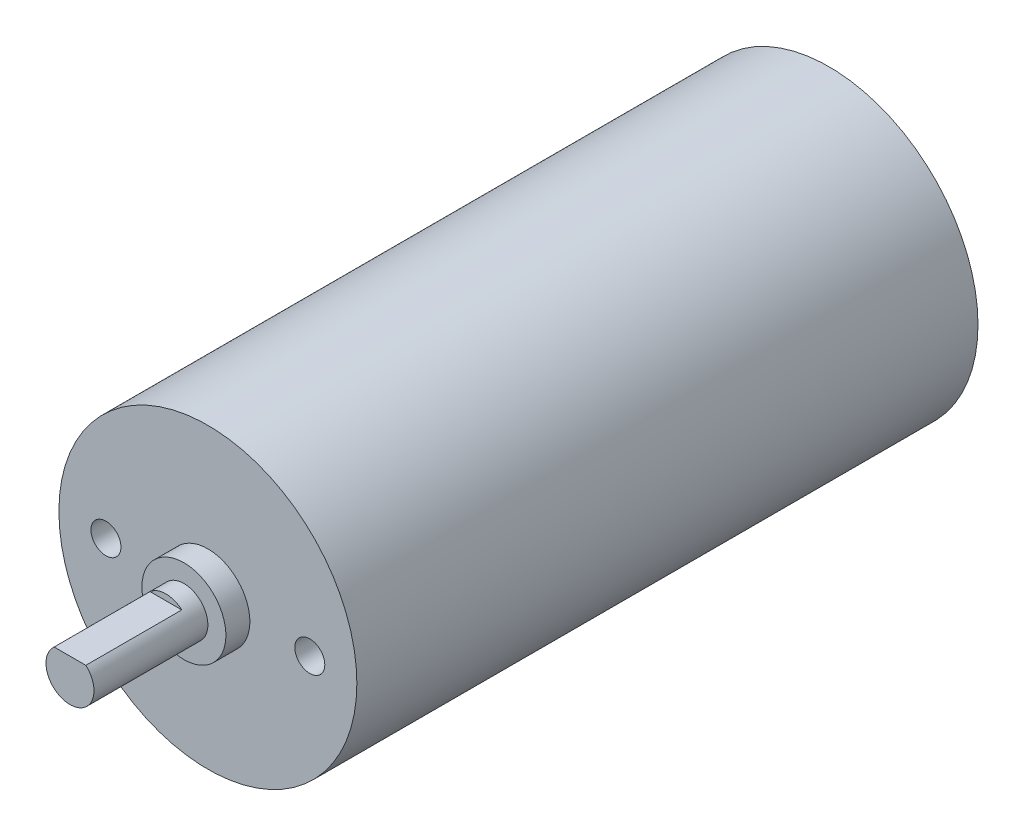
SolidWorks part; units mm, degrees
ref_plane "Front Plane" through (0, 0, 0) normal (0, 0, 1) x (1, 0, 0)
ref_plane "Top Plane" through (0, 0, 0) normal (0, 1, 0) x (1, 0, 0)
ref_plane "Right Plane" through (0, 0, 0) normal (1, 0, 0) x (0, 0, -1)
sketch "Sketch1" plane through (0, 0, 0) normal (0, 0, 1) x (1, 0, 0)
  line L0 (-1.3229, 1.5) -> (1.3229, 1.5)
  arc A0 (-1.3229, 1.5) -> (1.3229, 1.5) centre (0, 0) ccw
  dimension "D1" = 4
  dimension "D2" = 1.5
extrude "Boss-Extrude1" add sketch "Sketch1" along normal blind 8
sketch "Sketch2" plane through (0, 0, 0) normal (0, 0, -1) x (-1, 0, 0)
  circle A0 centre (0, 0) radius 2
  dimension "D1" = 4
extrude "Boss-Extrude2" add sketch "Sketch2" along normal blind 1.5
sketch "Sketch3" plane through (0, 0, -1.5) normal (0, 0, -1) x (-1, 0, 0)
  circle A0 centre (0, 0) radius 3.5
  dimension "D1" = 7
extrude "Boss-Extrude3" add sketch "Sketch3" along normal blind 2
sketch "Sketch4" plane through (0, 0, -3.5) normal (0, 0, -1) x (-1, 0, 0)
  circle A0 centre (0, 0) radius 12.425
  dimension "D1" = 24.85
extrude "Boss-Extrude4" add sketch "Sketch4" along normal blind 51.8
hole_wizard "M3 Tapped Hole1" positions "Sketch5" profile "Sketch6" tap size "M3" standard "ISO"
sketch "Sketch5" plane through (0, 0, -3.5) normal (0, 0, 1) x (1, 0, 0)
  point P8 (8.5, 0)
  point P10 (-8.5, 0)
  dimension "D1" = 8.5
  dimension "D2" = 17
sketch "Sketch6" plane through (8.5, 0, -3.5) normal (1, 0, 0) x (0, -1, 0)
  line L0 (0, 0) -> (0, 13.4511)
  line L1 (0, 13.4511) -> (1.25, 12.7)
  line L2 (1.25, 12.7) -> (1.25, 0)
  line L5 (1.25, 0) -> (0, 0)
  line L10 (0, 13.4511) -> (-1.25, 12.7) construction
  line L11 (0, -6.35) -> (0, 107.95) construction
  dimension "Tap Drill Dia." = 2.5
  dimension "Tap Drill Depth" = 12.7
  dimension "Drill Angle" = 118
cosmetic thread "Hole Thread1" parameters "D1"=6, "D2"=3
cosmetic thread "Hole Thread2" parameters "D1"=6, "D2"=3
